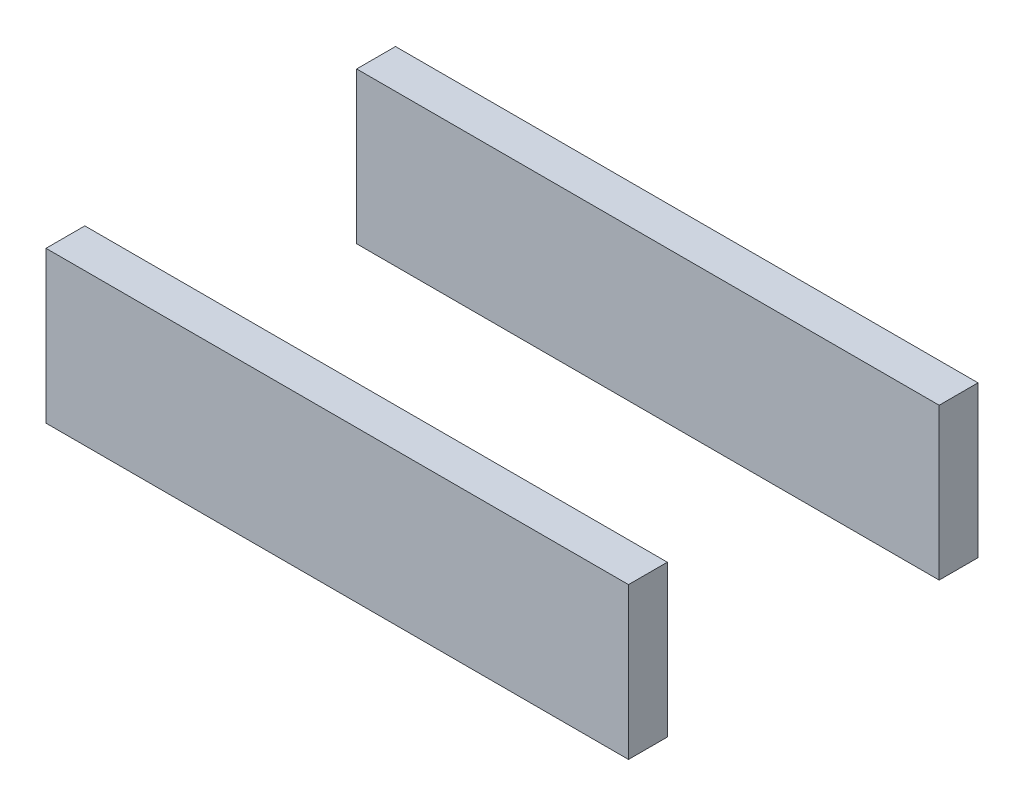
SolidWorks part; units mm, degrees
ref_plane "Front Plane" through (0, 0, 0) normal (0, 0, 1) x (1, 0, 0)
ref_plane "Top Plane" through (0, 0, 0) normal (0, 1, 0) x (1, 0, 0)
ref_plane "Right Plane" through (0, 0, 0) normal (1, 0, 0) x (0, 0, -1)
sketch "Sketch1" plane through (0, 0, 0) normal (0, 1, 0) x (1, 0, 0)
  line L1 (-25.5693, 37.338) -> (12.5307, 37.338)
  line L2 (-25.5693, 37.338) -> (-25.5693, 34.798)
  line L3 (-25.5693, 34.798) -> (12.5307, 34.798)
  line L4 (12.5307, 37.338) -> (12.5307, 34.798)
  line L5 (-25.5693, 17.018) -> (12.5307, 17.018)
  line L6 (-25.5693, 17.018) -> (-25.5693, 14.478)
  line L7 (-25.5693, 14.478) -> (12.5307, 14.478)
  line L8 (12.5307, 17.018) -> (12.5307, 14.478)
  dimension "D1" = 2.54
  dimension "D2" = 22.86
  dimension "D3" = 38.1
extrude "Boss-Extrude1" add sketch "Sketch1" along normal blind 9.906
